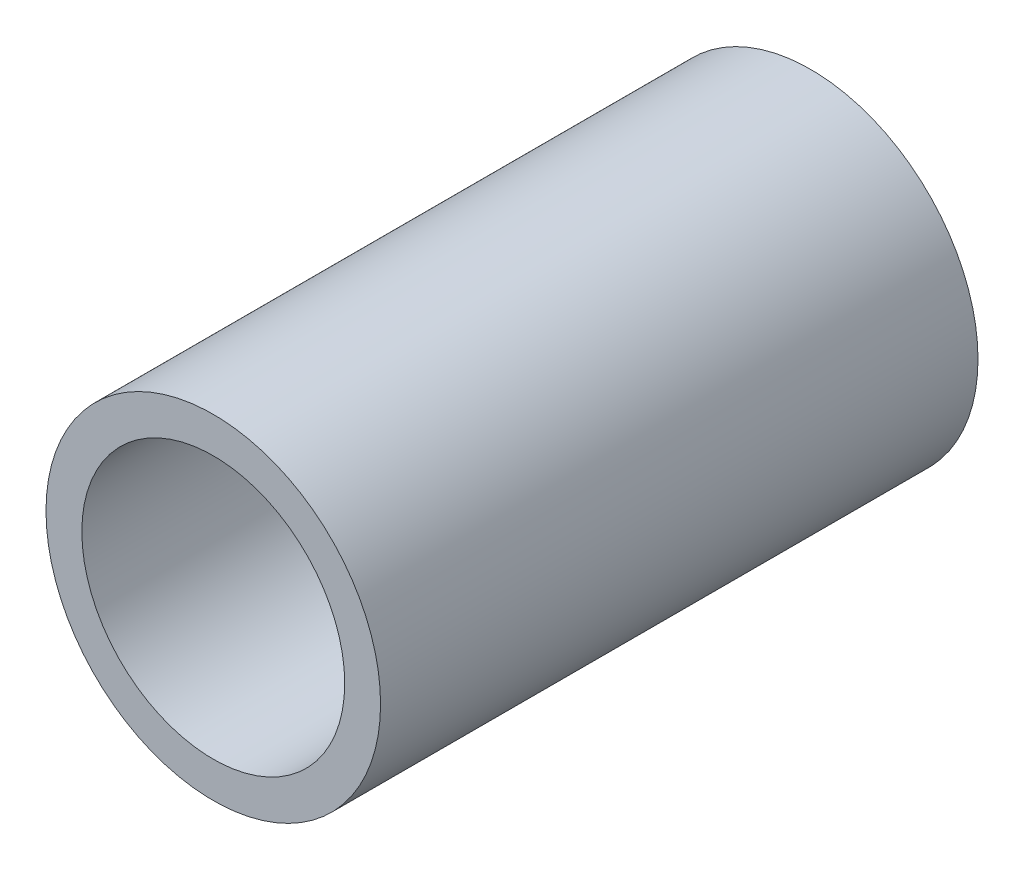
SolidWorks part; units mm, degrees
ref_plane "Plano frontal" through (0, 0, 0) normal (0, 0, 1) x (1, 0, 0)
ref_plane "Plano superior" through (0, 0, 0) normal (0, 1, 0) x (1, 0, 0)
ref_plane "Plano direito" through (0, 0, 0) normal (1, 0, 0) x (0, 0, -1)
sketch "Esboço1" plane through (0, 0, 0) normal (0, 0, 1) x (1, 0, 0)
  circle A0 centre (2.2536, 0) radius 11
  circle A1 centre (2.2536, 0) radius 14
extrude "Ressalto-extrusão1" add sketch "Esboço1" along normal blind 50
